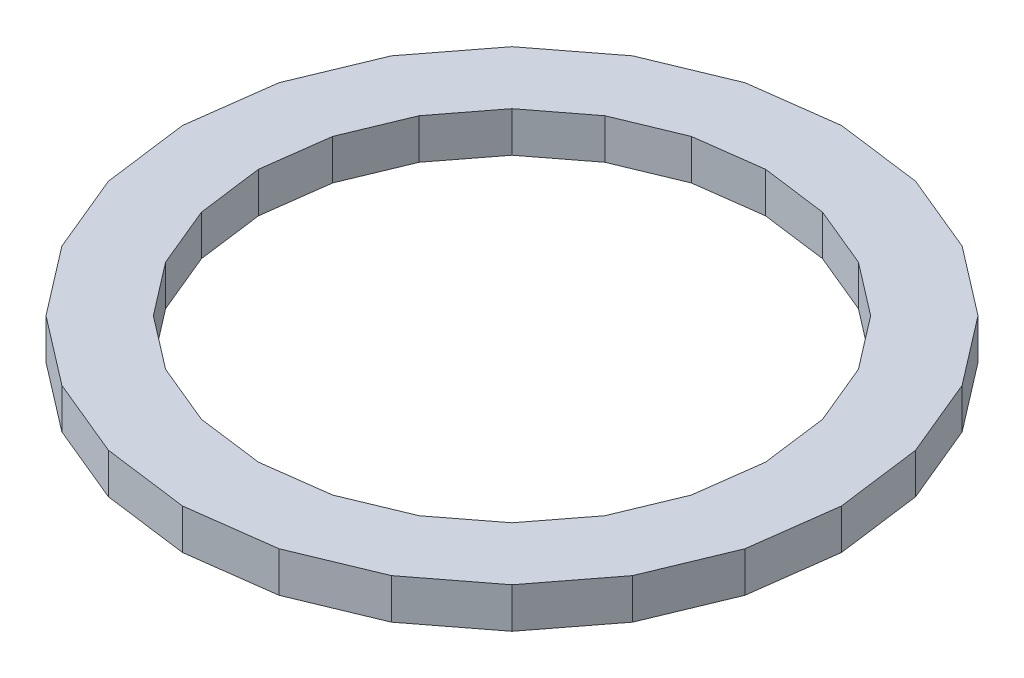
SolidWorks part; units mm, degrees
ref_plane "Front Plane" through (0, 0, 0) normal (0, 0, 1) x (1, 0, 0)
ref_plane "Top Plane" through (0, 0, 0) normal (0, 1, 0) x (1, 0, 0)
ref_plane "Right Plane" through (0, 0, 0) normal (1, 0, 0) x (0, 0, -1)
sketch "Sketch3" plane through (0, 0, 0) normal (0, 1, 0) x (1, 0, 0)
  line L0 (0, 0) -> (-119.8107, 0) construction
  line L1 (-155.6776, 0) -> (-150.373, -40.2923)
  line L2 (-150.373, -40.2923) -> (-134.8207, -77.8388)
  line L3 (-134.8207, -77.8388) -> (-110.0807, -110.0807)
  line L4 (-110.0807, -110.0807) -> (-77.8388, -134.8207)
  line L5 (-77.8388, -134.8207) -> (-40.2923, -150.373)
  line L6 (-40.2923, -150.373) -> (0, -155.6776)
  line L7 (0, -155.6776) -> (40.2923, -150.373)
  line L8 (40.2923, -150.373) -> (77.8388, -134.8207)
  line L9 (77.8388, -134.8207) -> (110.0807, -110.0807)
  line L10 (110.0807, -110.0807) -> (134.8207, -77.8388)
  line L11 (134.8207, -77.8388) -> (150.373, -40.2923)
  line L12 (150.373, -40.2923) -> (155.6776, 0)
  line L13 (155.6776, 0) -> (150.373, 40.2923)
  line L14 (150.373, 40.2923) -> (134.8207, 77.8388)
  line L15 (134.8207, 77.8388) -> (110.0807, 110.0807)
  line L16 (110.0807, 110.0807) -> (77.8388, 134.8207)
  line L17 (77.8388, 134.8207) -> (40.2923, 150.373)
  line L18 (40.2923, 150.373) -> (0, 155.6776)
  line L19 (0, 155.6776) -> (-40.2923, 150.373)
  line L20 (-40.2923, 150.373) -> (-77.8388, 134.8207)
  line L21 (-77.8388, 134.8207) -> (-110.0807, 110.0807)
  line L22 (-110.0807, 110.0807) -> (-134.8207, 77.8388)
  line L23 (-134.8207, 77.8388) -> (-150.373, 40.2923)
  line L24 (-150.373, 40.2923) -> (-155.6776, 0)
  line L25 (-119.8107, 0) -> (-115.7283, -31.0093)
  line L26 (-115.7283, -31.0093) -> (-103.7591, -59.9054)
  line L27 (-103.7591, -59.9054) -> (-84.719, -84.719)
  line L28 (-84.719, -84.719) -> (-59.9054, -103.7591)
  line L29 (-59.9054, -103.7591) -> (-31.0093, -115.7283)
  line L30 (-31.0093, -115.7283) -> (0, -119.8107)
  line L31 (0, -119.8107) -> (31.0093, -115.7283)
  line L32 (31.0093, -115.7283) -> (59.9054, -103.7591)
  line L33 (59.9054, -103.7591) -> (84.719, -84.719)
  line L34 (84.719, -84.719) -> (103.7591, -59.9054)
  line L35 (103.7591, -59.9054) -> (115.7283, -31.0093)
  line L36 (115.7283, -31.0093) -> (119.8107, 0)
  line L37 (119.8107, 0) -> (115.7283, 31.0093)
  line L38 (115.7283, 31.0093) -> (103.7591, 59.9054)
  line L39 (103.7591, 59.9054) -> (84.719, 84.719)
  line L40 (84.719, 84.719) -> (59.9054, 103.7591)
  line L41 (59.9054, 103.7591) -> (31.0093, 115.7283)
  line L42 (31.0093, 115.7283) -> (0, 119.8107)
  line L43 (0, 119.8107) -> (-31.0093, 115.7283)
  line L44 (-31.0093, 115.7283) -> (-59.9054, 103.7591)
  line L45 (-59.9054, 103.7591) -> (-84.719, 84.719)
  line L46 (-84.719, 84.719) -> (-103.7591, 59.9054)
  line L47 (-103.7591, 59.9054) -> (-115.7283, 31.0093)
  line L48 (-115.7283, 31.0093) -> (-119.8107, 0)
  line L49 (-155.6776, 0) -> (-119.8107, 0) construction
  circle A0 centre (0, 0) radius 154.3457 construction
  circle A1 centre (0, 0) radius 118.7857 construction
  dimension "D1" = 40.64
  dimension "D2" = 35.56
extrude "Boss-Extrude3" add sketch "Sketch3" along normal blind 19.05
